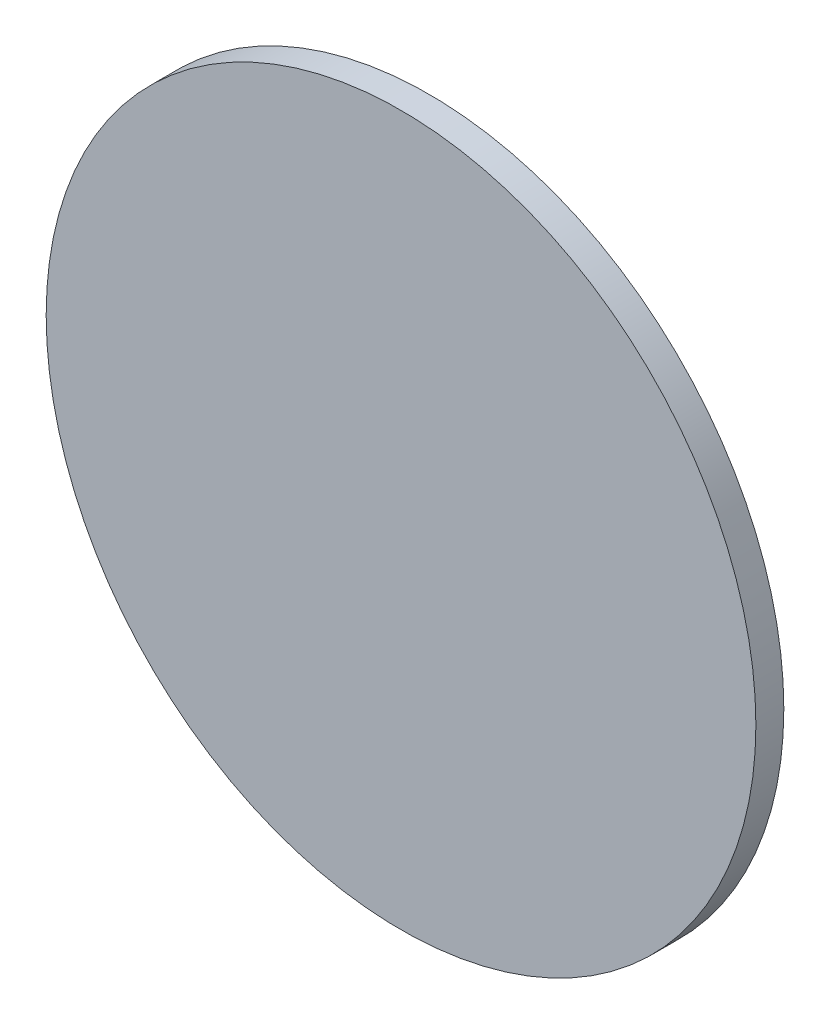
SolidWorks part; units mm, degrees
material "Manual Density from Real Component Motore FWD"
ref_plane "Piano frontale" through (0, 0, 0) normal (0, 0, 1) x (1, 0, 0)
ref_plane "Piano superiore" through (0, 0, 0) normal (0, 1, 0) x (1, 0, 0)
ref_plane "Piano destro" through (0, 0, 0) normal (1, 0, 0) x (0, 0, -1)
sketch "Schizzo1" plane through (0, 0, 0) normal (0, 0, 1) x (1, 0, 0)
  circle A0 centre (0, 0) radius 63.5
  dimension "D1" = 127
extrude "Estrusione-Estrusione1" add sketch "Schizzo1" along normal blind 5
